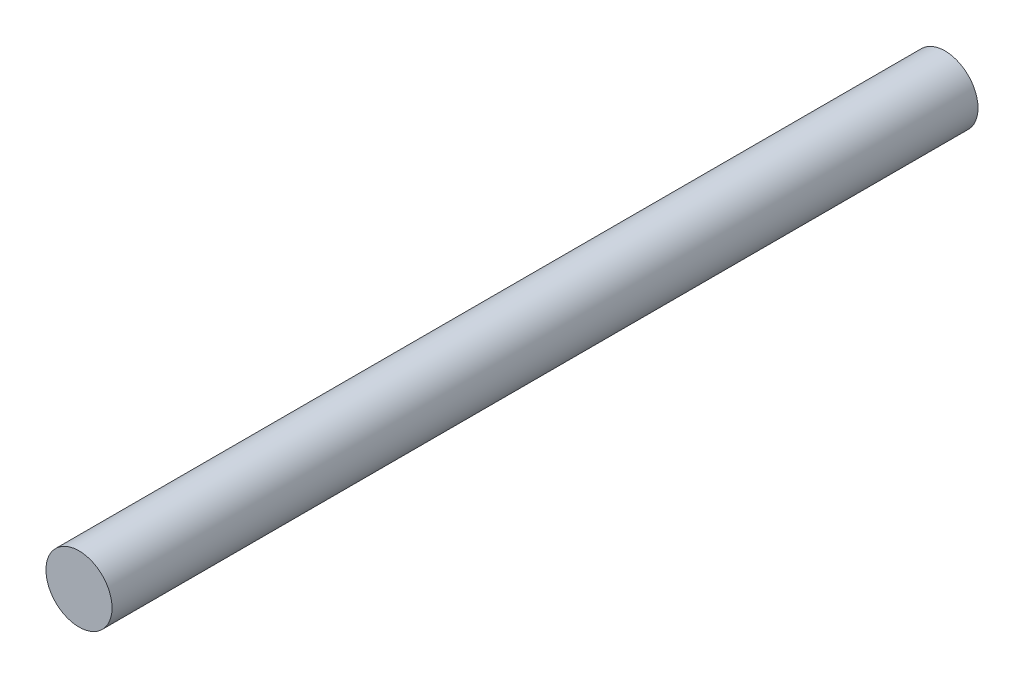
SolidWorks part; units mm, degrees
ref_plane "Front Plane" through (0, 0, 0) normal (0, 0, 1) x (1, 0, 0)
ref_plane "Top Plane" through (0, 0, 0) normal (0, 1, 0) x (1, 0, 0)
ref_plane "Right Plane" through (0, 0, 0) normal (1, 0, 0) x (0, 0, -1)
sketch "Sketch1" plane through (0, 0, 0) normal (0, 0, 1) x (1, 0, 0)
  circle A0 centre (0, 0) radius 10
extrude "Boss-Extrude1" add sketch "Sketch1" along normal blind 262
